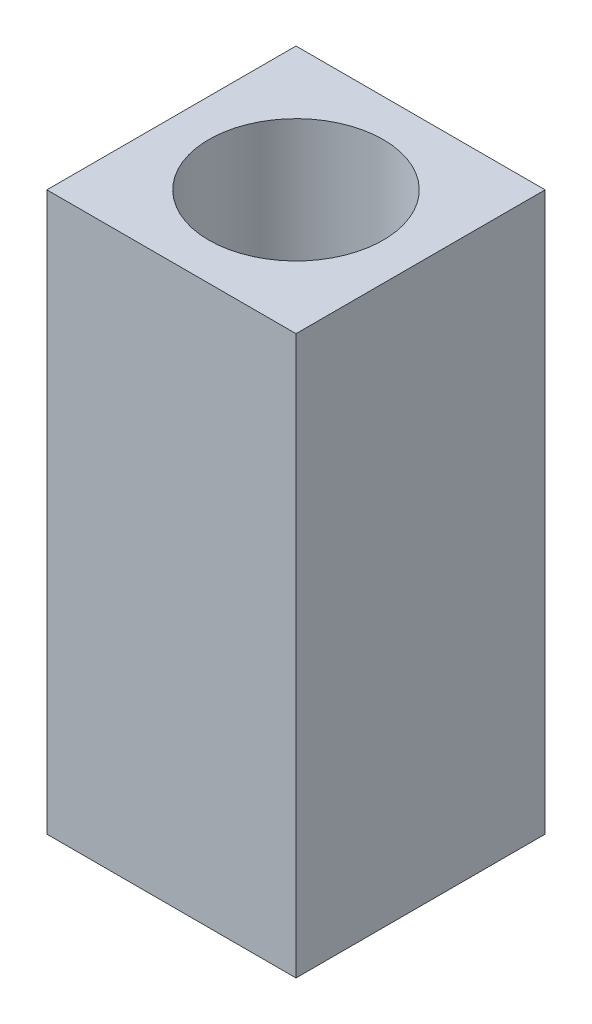
SolidWorks part; units mm, degrees
ref_plane "Płaszczyzna przednia" through (0, 0, 0) normal (0, 0, 1) x (1, 0, 0)
ref_plane "Płaszczyzna górna" through (0, 0, 0) normal (0, 1, 0) x (1, 0, 0)
ref_plane "Płaszczyzna prawa" through (0, 0, 0) normal (1, 0, 0) x (0, 0, -1)
sketch "Szkic1" plane through (0, 0, 0) normal (0, 1, 0) x (1, 0, 0)
  line L1 (-2.5, -2.5) -> (2.5, -2.5)
  line L2 (-2.5, -2.5) -> (-2.5, 2.5)
  line L3 (-2.5, 2.5) -> (2.5, 2.5)
  line L4 (2.5, -2.5) -> (2.5, 2.5)
  line L5 (-2.5, -2.5) -> (2.5, 2.5) construction
  line L6 (-2.5, 2.5) -> (2.5, -2.5) construction
  circle A0 centre (0, 0) radius 1.75
  dimension "D1" = 3.5
  dimension "D2" = 5
  dimension "D3" = 5
extrude "Dodanie-wyciągnięcie1" add sketch "Szkic1" along normal blind 11.2
